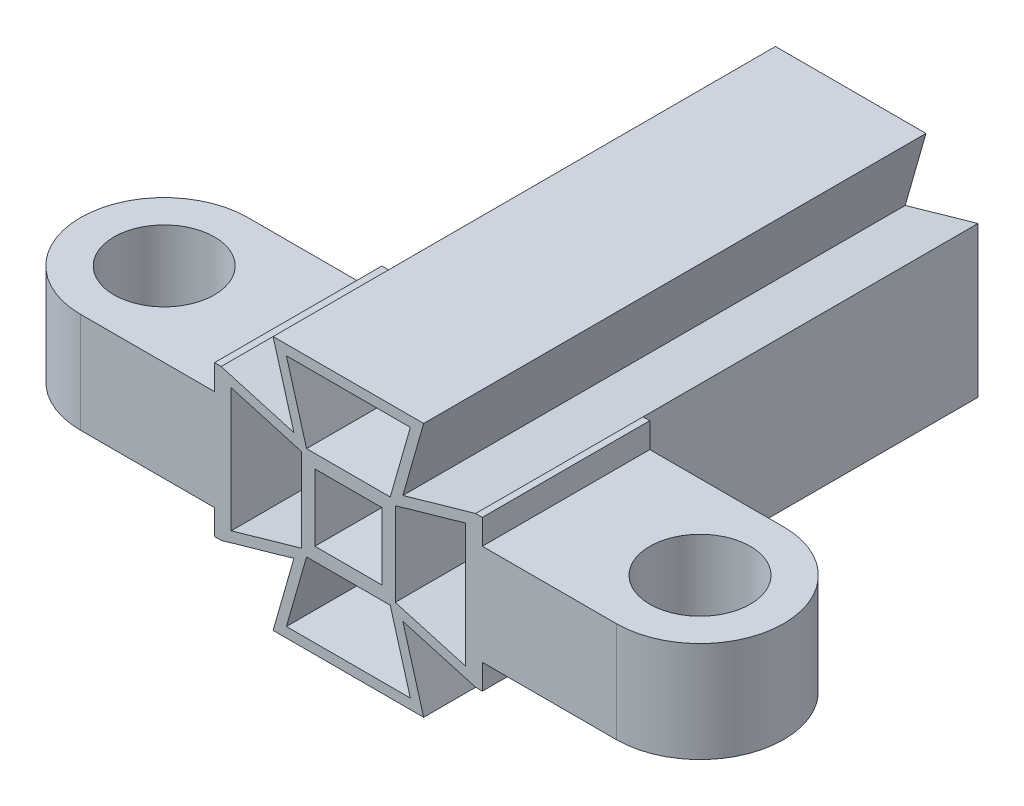
SolidWorks part; units mm, degrees
ref_plane "Front Plane" through (0, 0, 0) normal (0, 0, 1) x (1, 0, 0)
ref_plane "Top Plane" through (0, 0, 0) normal (0, 1, 0) x (1, 0, 0)
ref_plane "Right Plane" through (0, 0, 0) normal (1, 0, 0) x (0, 0, -1)
sketch "Sketch1" plane through (0, 0, 0) normal (0, 0, 1) x (1, 0, 0)
  line L0 (0, 45.5072) -> (0, -40.4348) construction
  line L1 (-48.8406, 0) -> (45.7971, 0) construction
  line L2 (12.5, 14) -> (-12.5, 14)
  line L3 (10, -10) -> (-10, -10)
  line L4 (10, -10) -> (10, 10)
  line L5 (10, 10) -> (-10, 10)
  line L6 (-10, -10) -> (-10, 10)
  line L7 (10, -10) -> (-10, 10) construction
  line L8 (10, 10) -> (-10, -10) construction
  line L13 (-12.5, 14) -> (-18.5, 35)
  line L14 (14, -12.5) -> (14, 12.5)
  line L15 (14, 12.5) -> (35, 18.5)
  line L16 (35, -18.5) -> (35, 18.5)
  line L17 (14, -12.5) -> (35, -18.5)
  line L18 (-12.5, -14) -> (12.5, -14)
  line L19 (12.5, -14) -> (18.5, -35)
  line L20 (-18.5, -35) -> (18.5, -35)
  line L21 (-12.5, -14) -> (-18.5, -35)
  line L22 (-14, 12.5) -> (-14, -12.5)
  line L23 (-14, -12.5) -> (-35, -18.5)
  line L24 (-35, 18.5) -> (-35, -18.5)
  line L25 (-14, 12.5) -> (-35, 18.5)
  line L26 (12.5, 14) -> (18.5, 35)
  line L27 (18.5, 35) -> (-18.5, 35)
  line L28 (22.4772, 38) -> (-22.4772, 38)
  line L32 (14.7629, 11) -> (-14.7629, 11) construction
  line L33 (38, -22.4772) -> (38, 22.4772)
  line L34 (16.2681, 16.2681) -> (38, 22.4772)
  line L35 (-16.2681, -16.2681) -> (-38, -22.4772)
  line L36 (-22.4772, -38) -> (22.4772, -38)
  line L37 (16.2681, -16.2681) -> (38, -22.4772)
  line L39 (-38, 22.4772) -> (-38, -22.4772)
  line L41 (16.2681, 16.2681) -> (22.4772, 38)
  line L42 (-16.2681, 16.2681) -> (-22.4772, 38)
  line L43 (-16.2681, 16.2681) -> (-38, 22.4772)
  line L44 (-14.7629, 11) -> (-22.4772, 38) construction
  line L46 (16.2681, -16.2681) -> (22.4772, -38)
  line L47 (14.7629, 11) -> (22.4772, 38) construction
  line L48 (-16.2681, -16.2681) -> (-22.4772, -38)
  point P5 (0, 0)
  point P10 (0, 0)
  point P13 (0, 14)
  point P14 (0, 35)
  point P19 (0, 35)
  dimension "D1" = 20
  dimension "D2" = 20
  dimension "D3" = 4
  dimension "D4" = 21
  dimension "D5" = 4
  dimension "D6" = 3
  dimension "D9" = 12.5
  dimension "D10" = 18.5
  dimension "D7" = 4
extrude "Boss-Extrude1" add sketch "Sketch1" along normal blind 150
sketch "Sketch2" plane through (0, 0, 0) normal (0, 0, 1) x (1, 0, 0)
  line L0 (0, 47.145) -> (0, -52.7539) construction
  line L1 (47.2966, 0) -> (-63.9717, 0) construction
  line L2 (18.5, 35) -> (-18.5, 35) construction
  line L3 (3.5, 35) -> (-3.5, 35)
  line L4 (3.5, 35) -> (3.5, 14)
  line L5 (3.5, 14) -> (-3.5, 14)
  line L6 (-3.5, 35) -> (-3.5, 14)
  line L7 (-12.5, 14) -> (12.5, 14) construction
  line L8 (35, -3.5) -> (14, -3.5)
  line L9 (35, -3.5) -> (35, 3.5)
  line L10 (35, 3.5) -> (14, 3.5)
  line L11 (14, -3.5) -> (14, 3.5)
  line L12 (-3.5, -35) -> (-3.5, -14)
  line L13 (-3.5, -35) -> (3.5, -35)
  line L14 (3.5, -35) -> (3.5, -14)
  line L15 (-3.5, -14) -> (3.5, -14)
  line L16 (-35, 3.5) -> (-14, 3.5)
  line L17 (-35, 3.5) -> (-35, -3.5)
  line L18 (-35, -3.5) -> (-14, -3.5)
  line L19 (-14, 3.5) -> (-14, -3.5)
  dimension "D1" = 7
  dimension "D2" = 3.5
  dimension "D3" = 4
extrude "Boss-Extrude2" add sketch "Sketch2" along normal blind 2
sketch "Sketch3" plane through (0, 0, 150) normal (0, 0, 1) x (1, 0, 0)
  line L0 (-46.9513, 0) -> (124.395, 0) construction
  line L1 (0, 54.3911) -> (0, -48.3881) construction
  line L2 (38, -22.4772) -> (38, 22.4772) construction
  line L3 (38, -22.4772) -> (38, 22.4772)
  line L4 (38, 22.4772) -> (40, 22.4772)
  line L5 (40, 22.4772) -> (40, 15)
  line L6 (40, 15) -> (105, 15)
  line L7 (105, 15) -> (105, -15)
  line L8 (38, -22.4772) -> (40, -22.4772)
  line L9 (40, -22.4772) -> (40, -15)
  line L10 (40, -15) -> (105, -15)
  line L11 (-38, -22.4772) -> (-40, -22.4772)
  line L12 (-40, -22.4772) -> (-40, -15)
  line L13 (-40, -15) -> (-105, -15)
  line L14 (-105, 15) -> (-105, -15)
  line L15 (-40, 15) -> (-105, 15)
  line L16 (-40, 22.4772) -> (-40, 15)
  line L17 (-38, 22.4772) -> (-40, 22.4772)
  line L18 (-38, -22.4772) -> (-38, 22.4772)
  point P12 (105, 0)
  line M15 (-38, 22.4772) -> (-38, -22.4772)
  line M21 (38, -22.4772) -> (38, 22.4772)
  dimension "D1" = 65
  dimension "D2" = 15
  dimension "D3" = 2
extrude "Boss-Extrude3" add sketch "Sketch3" against normal blind 50 contours L9 L10 L7 L6 L5 L4 L8 M21 | L17 L16 L15 L14 L13 L12 L11 M15
sketch "Sketch4" plane through (0, 15, 0) normal (0, 1, 0) x (1, 0, 0)
  line L0 (0, 32.0453) -> (0, -172.5489) construction
  line L1 (22.4772, -150) -> (-22.4772, -150) construction
  line L2 (80, -100) -> (80, -91.9063)
  line L3 (80, -91.9063) -> (116.2372, -91.9063)
  line L4 (116.2372, -91.9063) -> (116.2372, -153.7945)
  line L5 (116.2372, -153.7945) -> (80, -153.7945)
  line L6 (80, -153.7945) -> (80, -150)
  line L7 (-80, -153.7945) -> (-80, -150)
  line L8 (-116.2372, -153.7945) -> (-80, -153.7945)
  line L9 (-116.2372, -91.9063) -> (-116.2372, -153.7945)
  line L10 (-80, -91.9063) -> (-116.2372, -91.9063)
  line L11 (-80, -100) -> (-80, -91.9063)
  arc A0 (80, -150) -> (80, -100) centre (80, -125) ccw
  circle A1 centre (80, -125) radius 15
  arc A2 (-80, -150) -> (-80, -100) centre (-80, -125) cw
  circle A3 centre (-80, -125) radius 15
  dimension "D1" = 50
  dimension "D2" = 25
  dimension "D4" = 30
  dimension "D3" = 80
extrude "Cut-Extrude1" cut sketch "Sketch4" against normal blind 50
